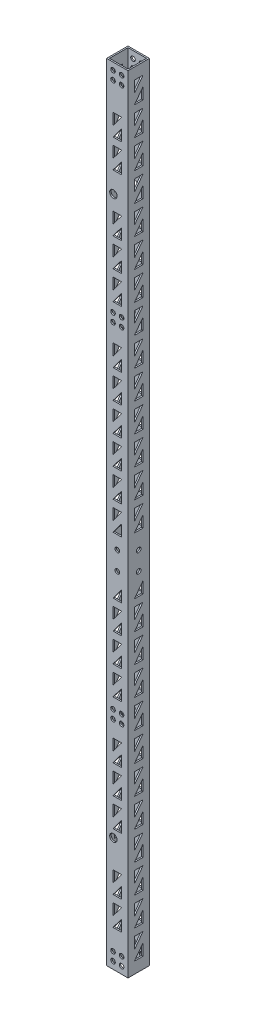
SolidWorks part; units mm, degrees
ref_plane "前视基准面" through (0, 0, 0) normal (0, 0, 1) x (1, 0, 0)
ref_plane "上视基准面" through (0, 0, 0) normal (0, 1, 0) x (1, 0, 0)
ref_plane "右视基准面" through (0, 0, 0) normal (1, 0, 0) x (0, 0, -1)
other "Configuration Table"
sketch "草图1" plane through (0, 0, 0) normal (0, 1, 0) x (1, 0, 0)
  line L1 (6.5, -6.5) -> (-6.5, -6.5)
  line L2 (6.5, -6.5) -> (6.5, 6.5)
  line L3 (6.5, 6.5) -> (-6.5, 6.5)
  line L4 (-6.5, -6.5) -> (-6.5, 6.5)
  line L5 (6.5, -6.5) -> (-6.5, 6.5) construction
  line L6 (6.5, 6.5) -> (-6.5, -6.5) construction
  line L7 (7.5, -7.5) -> (-7.5, -7.5)
  line L8 (7.5, -7.5) -> (7.5, 7.5)
  line L9 (7.5, 7.5) -> (-7.5, 7.5)
  line L10 (-7.5, -7.5) -> (-7.5, 7.5)
  line L11 (7.5, -7.5) -> (-7.5, 7.5) construction
  line L12 (7.5, 7.5) -> (-7.5, -7.5) construction
  point P0 (0, 0)
  point P6 (0, 0)
  dimension "D1" = 13
  dimension "D2" = 15
extrude "凸台-拉伸1" add sketch "草图1" along normal blind 551
sketch "草图2" plane through (0, 0, 7.5) normal (0, 0, 1) x (1, 0, 0)
  line L0 (-7.5, 543) -> (7.5, 543) construction
  line L1 (-7.5, 551) -> (-7.5, 0) construction
  line L2 (7.5, 551) -> (7.5, 0) construction
  line L3 (-7.5, 275.5) -> (7.5, 275.5) construction
  line L4 (-7.5, 551) -> (7.5, 551) construction
  line L5 (0, 549.2213) -> (0, 545.4151) construction
  line L6 (-7.5, 525.5) -> (7.5, 525.5) construction
  line L7 (-7.5, 25.5) -> (7.5, 25.5) construction
  line L8 (-3, 512.5) -> (-3, 520.5)
  line L9 (-3, 520.5) -> (3, 520.5)
  line L10 (3, 520.5) -> (-3, 512.5)
  line L11 (-3, 505.5) -> (3, 505.5)
  line L12 (3, 505.5) -> (3, 513.5)
  line L13 (3, 513.5) -> (-3, 505.5)
  line L14 (3, 500.5) -> (-3, 492.5)
  line L15 (-3, 492.5) -> (-3, 500.5)
  line L16 (-3, 500.5) -> (3, 500.5)
  line L17 (3, 493.5) -> (-3, 485.5)
  line L18 (-3, 485.5) -> (3, 485.5)
  line L19 (3, 485.5) -> (3, 493.5)
  line L26 (3, 460.5) -> (-3, 452.5)
  line L27 (-3, 452.5) -> (-3, 460.5)
  line L28 (-3, 460.5) -> (3, 460.5)
  line L29 (3, 453.5) -> (-3, 445.5)
  line L30 (-3, 445.5) -> (3, 445.5)
  line L31 (3, 445.5) -> (3, 453.5)
  line L32 (3, 440.5) -> (-3, 432.5)
  line L33 (-3, 432.5) -> (-3, 440.5)
  line L34 (-3, 440.5) -> (3, 440.5)
  line L35 (3, 433.5) -> (-3, 425.5)
  line L36 (-3, 425.5) -> (3, 425.5)
  line L37 (3, 425.5) -> (3, 433.5)
  line L38 (3, 420.5) -> (-3, 412.5)
  line L39 (-3, 412.5) -> (-3, 420.5)
  line L40 (-3, 420.5) -> (3, 420.5)
  line L41 (3, 413.5) -> (-3, 405.5)
  line L42 (-3, 405.5) -> (3, 405.5)
  line L43 (3, 405.5) -> (3, 413.5)
  line L50 (3, 380.5) -> (-3, 372.5)
  line L51 (-3, 372.5) -> (-3, 380.5)
  line L52 (-3, 380.5) -> (3, 380.5)
  line L53 (3, 373.5) -> (-3, 365.5)
  line L54 (-3, 365.5) -> (3, 365.5)
  line L55 (3, 365.5) -> (3, 373.5)
  line L56 (3, 360.5) -> (-3, 352.5)
  line L57 (-3, 352.5) -> (-3, 360.5)
  line L58 (-3, 360.5) -> (3, 360.5)
  line L59 (3, 353.5) -> (-3, 345.5)
  line L60 (-3, 345.5) -> (3, 345.5)
  line L61 (3, 345.5) -> (3, 353.5)
  line L62 (3, 340.5) -> (-3, 332.5)
  line L63 (-3, 332.5) -> (-3, 340.5)
  line L64 (-3, 340.5) -> (3, 340.5)
  line L65 (3, 333.5) -> (-3, 325.5)
  line L66 (-3, 325.5) -> (3, 325.5)
  line L67 (3, 325.5) -> (3, 333.5)
  line L68 (3, 320.5) -> (-3, 312.5)
  line L69 (-3, 312.5) -> (-3, 320.5)
  line L70 (-3, 320.5) -> (3, 320.5)
  line L71 (3, 313.5) -> (-3, 305.5)
  line L72 (-3, 305.5) -> (3, 305.5)
  line L73 (3, 305.5) -> (3, 313.5)
  line L74 (3, 300.5) -> (-3, 292.5)
  line L75 (-3, 292.5) -> (-3, 300.5)
  line L76 (-3, 300.5) -> (3, 300.5)
  line L77 (3, 293.5) -> (-3, 285.5)
  line L78 (-3, 285.5) -> (3, 285.5)
  line L79 (3, 285.5) -> (3, 293.5)
  line L80 (3, 280.5) -> (-3, 272.5)
  line L81 (-3, 272.5) -> (-3, 280.5)
  line L82 (-3, 280.5) -> (3, 280.5)
  line L83 (3, 273.5) -> (-3, 265.5)
  line L84 (-3, 265.5) -> (3, 265.5)
  line L85 (3, 265.5) -> (3, 273.5)
  line L95 (3, 233.5) -> (-3, 225.5)
  line L96 (-3, 225.5) -> (3, 225.5)
  line L97 (3, 225.5) -> (3, 233.5)
  line L98 (3, 220.5) -> (-3, 212.5)
  line L99 (-3, 212.5) -> (-3, 220.5)
  line L100 (-3, 220.5) -> (3, 220.5)
  line L101 (3, 213.5) -> (-3, 205.5)
  line L102 (-3, 205.5) -> (3, 205.5)
  line L103 (3, 205.5) -> (3, 213.5)
  line L104 (3, 200.5) -> (-3, 192.5)
  line L105 (-3, 192.5) -> (-3, 200.5)
  line L106 (-3, 200.5) -> (3, 200.5)
  line L107 (3, 193.5) -> (-3, 185.5)
  line L108 (-3, 185.5) -> (3, 185.5)
  line L109 (3, 185.5) -> (3, 193.5)
  line L110 (3, 180.5) -> (-3, 172.5)
  line L111 (-3, 172.5) -> (-3, 180.5)
  line L112 (-3, 180.5) -> (3, 180.5)
  line L113 (3, 173.5) -> (-3, 165.5)
  line L114 (-3, 165.5) -> (3, 165.5)
  line L115 (3, 165.5) -> (3, 173.5)
  line L122 (3, 140.5) -> (-3, 132.5)
  line L123 (-3, 132.5) -> (-3, 140.5)
  line L124 (-3, 140.5) -> (3, 140.5)
  line L125 (3, 133.5) -> (-3, 125.5)
  line L126 (-3, 125.5) -> (3, 125.5)
  line L127 (3, 125.5) -> (3, 133.5)
  line L128 (3, 120.5) -> (-3, 112.5)
  line L129 (-3, 112.5) -> (-3, 120.5)
  line L130 (-3, 120.5) -> (3, 120.5)
  line L131 (3, 113.5) -> (-3, 105.5)
  line L132 (-3, 105.5) -> (3, 105.5)
  line L133 (3, 105.5) -> (3, 113.5)
  line L134 (3, 100.5) -> (-3, 92.5)
  line L135 (-3, 92.5) -> (-3, 100.5)
  line L136 (-3, 100.5) -> (3, 100.5)
  line L137 (3, 93.5) -> (-3, 85.5)
  line L138 (-3, 85.5) -> (3, 85.5)
  line L139 (3, 85.5) -> (3, 93.5)
  line L146 (3, 60.5) -> (-3, 52.5)
  line L147 (-3, 52.5) -> (-3, 60.5)
  line L148 (-3, 60.5) -> (3, 60.5)
  line L149 (3, 53.5) -> (-3, 45.5)
  line L150 (-3, 45.5) -> (3, 45.5)
  line L151 (3, 45.5) -> (3, 53.5)
  line L152 (3, 40.5) -> (-3, 32.5)
  line L153 (-3, 32.5) -> (-3, 40.5)
  line L154 (-3, 40.5) -> (3, 40.5)
  line L155 (3, 33.5) -> (-3, 25.5)
  line L156 (-3, 25.5) -> (3, 25.5)
  line L157 (3, 25.5) -> (3, 33.5)
  line L158 (3, 253.5) -> (-3, 245.5) [skipped]
  line L159 (3, 245.5) -> (3, 253.5) [skipped]
  line L160 (-3, 245.5) -> (3, 245.5) [skipped]
  line L161 (-3, 252.5) -> (-3, 260.5) [skipped]
  line L162 (-3, 260.5) -> (3, 260.5) [skipped]
  line L163 (3, 260.5) -> (-3, 252.5) [skipped]
  line L164 (-3, 232.5) -> (-3, 240.5) [skipped]
  line L165 (-3, 240.5) -> (3, 240.5) [skipped]
  line L166 (3, 240.5) -> (-3, 232.5) [skipped]
  line L167 (3, 400.5) -> (-3, 392.5) [skipped]
  line L168 (-3, 400.5) -> (3, 400.5) [skipped]
  line L169 (-3, 392.5) -> (-3, 400.5) [skipped]
  line L170 (-3, 160.5) -> (3, 160.5) [skipped]
  line L171 (3, 160.5) -> (-3, 152.5) [skipped]
  line L172 (-3, 152.5) -> (-3, 160.5) [skipped]
  line L173 (-7.5, 396) -> (7.5, 396) construction
  line L174 (-7.5, 155) -> (7.5, 155) construction
  line L175 (-3, 480.5) -> (3, 480.5) [skipped]
  line L176 (3, 480.5) -> (-3, 472.5) [skipped]
  line L177 (-3, 472.5) -> (-3, 480.5) [skipped]
  line L178 (3, 473.5) -> (-3, 465.5) [skipped]
  line L179 (-3, 465.5) -> (3, 465.5) [skipped]
  line L180 (3, 465.5) -> (3, 473.5) [skipped]
  line L181 (-3, 80.5) -> (3, 80.5) [skipped]
  line L182 (3, 80.5) -> (-3, 72.5) [skipped]
  line L183 (-3, 72.5) -> (-3, 80.5) [skipped]
  line L184 (3, 73.5) -> (-3, 65.5) [skipped]
  line L185 (3, 65.5) -> (3, 73.5) [skipped]
  line L186 (-3, 65.5) -> (3, 65.5) [skipped]
  line L187 (3, 393.5) -> (-3, 385.5) [skipped]
  line L188 (-3, 385.5) -> (3, 385.5) [skipped]
  line L189 (3, 385.5) -> (3, 393.5) [skipped]
  line L190 (3, 153.5) -> (-3, 145.5) [skipped]
  line L191 (-3, 145.5) -> (3, 145.5) [skipped]
  line L192 (3, 145.5) -> (3, 153.5) [skipped]
  circle A0 centre (-3, 546) radius 1.6
  circle A1 centre (3, 546) radius 1.6
  circle A2 centre (-3, 540) radius 1.6
  circle A3 centre (3, 540) radius 1.6
  circle A4 centre (3, 11) radius 1.6
  circle A5 centre (-3, 11) radius 1.6
  circle A6 centre (3, 5) radius 1.6
  circle A7 centre (-3, 5) radius 1.6
  circle A9 centre (0, 256.2) radius 1.6
  circle A10 centre (0, 243.2) radius 1.6
  circle A11 centre (-2.75, 471) radius 2.6
  circle A12 centre (-2.75, 80) radius 2.6
  circle A13 centre (-3, 399) radius 1.6
  circle A14 centre (-3, 393) radius 1.6
  circle A15 centre (3, 393) radius 1.6
  circle A16 centre (3, 399) radius 1.6
  circle A17 centre (3, 152) radius 1.6
  circle A18 centre (3, 158) radius 1.6
  circle A19 centre (-3, 158) radius 1.6
  circle A20 centre (-3, 152) radius 1.6
  dimension "D2" = 3.2
  dimension "D6" = 3.2
  dimension "D16" = 5.2
  dimension "D20" = 3.2
  dimension "D1" = 8
  dimension "D3" = 6
  dimension "D4" = 6
  dimension "D5" = 25.5
  dimension "D7" = 294.8
  dimension "D8" = 13
  dimension "D9" = 6
  dimension "D10" = 8
  dimension "D11" = 5
  dimension "D12" = 8
  dimension "D13" = 6
  dimension "D14" = 15
  dimension "D17" = 80
  dimension "D18" = 4.75
  dimension "D19" = 155
  dimension "D21" = 3
  dimension "D22" = 3
  dimension "D15" = 25
extrude "切除-拉伸1" cut sketch "草图2" against normal up to surface (15 mm away) up to face at (0, 275.5, -7.5)
sketch "草图4" plane through (7.5, 0, 0) normal (1, 0, 0) x (0, 0, -1)
  line L0 (0, 279.6032) -> (0, 248.1841) construction
  line L1 (-7.5, 551) -> (7.5, 551) construction
  line L2 (-3, 543) -> (3, 543)
  line L3 (3, 543) -> (-3, 535)
  line L4 (-3, 535) -> (-3, 543)
  line L5 (-3, 528) -> (3, 536)
  line L6 (3, 536) -> (3, 528)
  line L7 (3, 528) -> (-3, 528)
  line L8 (-3, 515) -> (-3, 523)
  line L9 (-3, 523) -> (3, 523)
  line L10 (3, 523) -> (-3, 515)
  line L11 (3, 508) -> (-3, 508)
  line L12 (-3, 508) -> (3, 516)
  line L13 (3, 516) -> (3, 508)
  line L14 (-3, 495) -> (-3, 503)
  line L15 (-3, 503) -> (3, 503)
  line L16 (3, 503) -> (-3, 495)
  line L17 (3, 488) -> (-3, 488)
  line L18 (-3, 488) -> (3, 496)
  line L19 (3, 496) -> (3, 488)
  line L20 (-3, 475) -> (-3, 483)
  line L21 (-3, 483) -> (3, 483)
  line L22 (3, 483) -> (-3, 475)
  line L23 (3, 468) -> (-3, 468)
  line L24 (-3, 468) -> (3, 476)
  line L25 (3, 476) -> (3, 468)
  line L26 (-3, 455) -> (-3, 463)
  line L27 (-3, 463) -> (3, 463)
  line L28 (3, 463) -> (-3, 455)
  line L29 (3, 448) -> (-3, 448)
  line L30 (-3, 448) -> (3, 456)
  line L31 (3, 456) -> (3, 448)
  line L32 (-3, 435) -> (-3, 443)
  line L33 (-3, 443) -> (3, 443)
  line L34 (3, 443) -> (-3, 435)
  line L35 (3, 428) -> (-3, 428)
  line L36 (-3, 428) -> (3, 436)
  line L37 (3, 436) -> (3, 428)
  line L38 (-3, 415) -> (-3, 423)
  line L39 (-3, 423) -> (3, 423)
  line L40 (3, 423) -> (-3, 415)
  line L41 (3, 408) -> (-3, 408)
  line L42 (-3, 408) -> (3, 416)
  line L43 (3, 416) -> (3, 408)
  line L44 (-3, 395) -> (-3, 403)
  line L45 (-3, 403) -> (3, 403)
  line L46 (3, 403) -> (-3, 395)
  line L47 (3, 388) -> (-3, 388)
  line L48 (-3, 388) -> (3, 396)
  line L49 (3, 396) -> (3, 388)
  line L50 (-3, 375) -> (-3, 383)
  line L51 (-3, 383) -> (3, 383)
  line L52 (3, 383) -> (-3, 375)
  line L53 (3, 368) -> (-3, 368)
  line L54 (-3, 368) -> (3, 376)
  line L55 (3, 376) -> (3, 368)
  line L56 (-3, 355) -> (-3, 363)
  line L57 (-3, 363) -> (3, 363)
  line L58 (3, 363) -> (-3, 355)
  line L59 (3, 348) -> (-3, 348)
  line L60 (-3, 348) -> (3, 356)
  line L61 (3, 356) -> (3, 348)
  line L62 (-3, 335) -> (-3, 343)
  line L63 (-3, 343) -> (3, 343)
  line L64 (3, 343) -> (-3, 335)
  line L65 (3, 328) -> (-3, 328)
  line L66 (-3, 328) -> (3, 336)
  line L67 (3, 336) -> (3, 328)
  line L68 (-3, 315) -> (-3, 323)
  line L69 (-3, 323) -> (3, 323)
  line L70 (3, 323) -> (-3, 315)
  line L71 (3, 308) -> (-3, 308)
  line L72 (-3, 308) -> (3, 316)
  line L73 (3, 316) -> (3, 308)
  line L74 (-3, 295) -> (-3, 303)
  line L75 (-3, 303) -> (3, 303)
  line L76 (3, 303) -> (-3, 295)
  line L77 (3, 288) -> (-3, 288)
  line L78 (-3, 288) -> (3, 296)
  line L79 (3, 296) -> (3, 288)
  line L80 (-3, 275) -> (-3, 283)
  line L81 (-3, 283) -> (3, 283)
  line L82 (3, 283) -> (-3, 275)
  line L83 (3, 268) -> (-3, 268)
  line L84 (-3, 268) -> (3, 276)
  line L85 (3, 276) -> (3, 268)
  line L95 (3, 228) -> (-3, 228)
  line L96 (-3, 228) -> (3, 236)
  line L97 (3, 236) -> (3, 228)
  line L98 (-3, 215) -> (-3, 223)
  line L99 (-3, 223) -> (3, 223)
  line L100 (3, 223) -> (-3, 215)
  line L101 (3, 208) -> (-3, 208)
  line L102 (-3, 208) -> (3, 216)
  line L103 (3, 216) -> (3, 208)
  line L104 (-3, 195) -> (-3, 203)
  line L105 (-3, 203) -> (3, 203)
  line L106 (3, 203) -> (-3, 195)
  line L107 (3, 188) -> (-3, 188)
  line L108 (-3, 188) -> (3, 196)
  line L109 (3, 196) -> (3, 188)
  line L110 (-3, 175) -> (-3, 183)
  line L111 (-3, 183) -> (3, 183)
  line L112 (3, 183) -> (-3, 175)
  line L113 (3, 168) -> (-3, 168)
  line L114 (-3, 168) -> (3, 176)
  line L115 (3, 176) -> (3, 168)
  line L116 (-3, 155) -> (-3, 163)
  line L117 (-3, 163) -> (3, 163)
  line L118 (3, 163) -> (-3, 155)
  line L119 (3, 148) -> (-3, 148)
  line L120 (-3, 148) -> (3, 156)
  line L121 (3, 156) -> (3, 148)
  line L122 (-3, 135) -> (-3, 143)
  line L123 (-3, 143) -> (3, 143)
  line L124 (3, 143) -> (-3, 135)
  line L125 (3, 128) -> (-3, 128)
  line L126 (-3, 128) -> (3, 136)
  line L127 (3, 136) -> (3, 128)
  line L128 (-3, 115) -> (-3, 123)
  line L129 (-3, 123) -> (3, 123)
  line L130 (3, 123) -> (-3, 115)
  line L131 (3, 108) -> (-3, 108)
  line L132 (-3, 108) -> (3, 116)
  line L133 (3, 116) -> (3, 108)
  line L134 (-3, 95) -> (-3, 103)
  line L135 (-3, 103) -> (3, 103)
  line L136 (3, 103) -> (-3, 95)
  line L137 (3, 88) -> (-3, 88)
  line L138 (-3, 88) -> (3, 96)
  line L139 (3, 96) -> (3, 88)
  line L140 (-3, 75) -> (-3, 83)
  line L141 (-3, 83) -> (3, 83)
  line L142 (3, 83) -> (-3, 75)
  line L143 (3, 68) -> (-3, 68)
  line L144 (-3, 68) -> (3, 76)
  line L145 (3, 76) -> (3, 68)
  line L146 (-3, 55) -> (-3, 63)
  line L147 (-3, 63) -> (3, 63)
  line L148 (3, 63) -> (-3, 55)
  line L149 (3, 48) -> (-3, 48)
  line L150 (-3, 48) -> (3, 56)
  line L151 (3, 56) -> (3, 48)
  line L152 (-3, 35) -> (-3, 43)
  line L153 (-3, 43) -> (3, 43)
  line L154 (3, 43) -> (-3, 35)
  line L155 (3, 28) -> (-3, 28)
  line L156 (-3, 28) -> (3, 36)
  line L157 (3, 36) -> (3, 28)
  line L158 (-3, 15) -> (-3, 23)
  line L159 (-3, 23) -> (3, 23)
  line L160 (3, 23) -> (-3, 15)
  line L161 (3, 8) -> (-3, 8)
  line L162 (-3, 8) -> (3, 16)
  line L163 (3, 16) -> (3, 8)
  line L166 (-3, 255) -> (-3, 263) [skipped]
  line L167 (-3, 263) -> (3, 263) [skipped]
  line L168 (3, 263) -> (-3, 255) [skipped]
  line L169 (-3, 248) -> (3, 256) [skipped]
  line L170 (3, 256) -> (3, 248) [skipped]
  line L171 (3, 248) -> (-3, 248) [skipped]
  line L172 (-3, 243) -> (3, 243) [skipped]
  line L173 (3, 243) -> (-3, 235) [skipped]
  line L174 (-3, 235) -> (-3, 243) [skipped]
  circle A0 centre (0, 256.2) radius 1.6
  circle A1 centre (0, 243.2) radius 1.6
  point P14 (0, 528)
  dimension "D1" = 3.2
  dimension "D2" = 294.8
  dimension "D3" = 13
  dimension "D4" = 3
  dimension "D5" = 3
  dimension "D6" = 8
  dimension "D7" = 8
  dimension "D8" = 6
  dimension "D9" = 8
  dimension "D10" = 15
  dimension "D11" = 3
  dimension "D12" = 27
extrude "切除-拉伸2" cut sketch "草图4" against normal up to surface (15 mm away) up to face at (-7.5, 275.5, 0)
